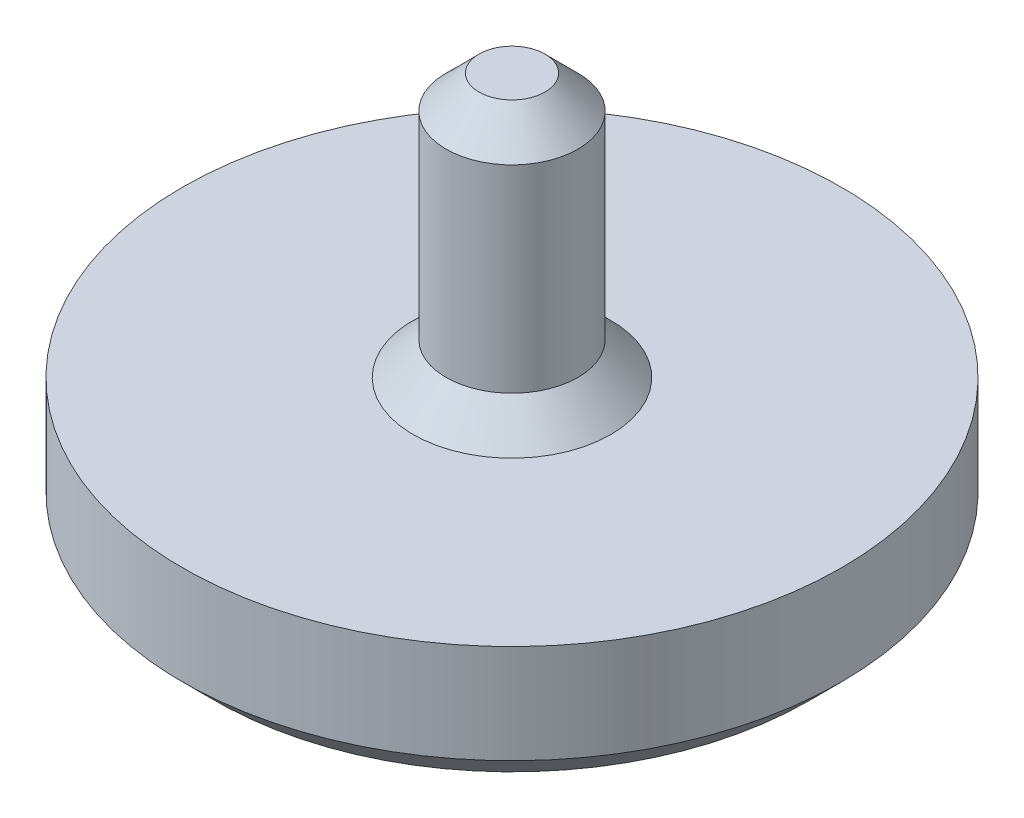
SolidWorks part; units mm, degrees
ref_plane "Front Plane" through (0, 0, 0) normal (0, 0, 1) x (1, 0, 0)
ref_plane "Top Plane" through (0, 0, 0) normal (0, 1, 0) x (1, 0, 0)
ref_plane "Right Plane" through (0, 0, 0) normal (1, 0, 0) x (0, 0, -1)
sketch "Sketch1" plane through (0, 0, 0) normal (0, 0, 1) x (1, 0, 0)
  line L0 (0, 0) -> (0, 4) construction
  line L1 (0, -55) -> (0, 55) construction
  line L2 (0, 4) -> (-1, 4)
  line L3 (-1, 4) -> (-1, 0)
  line L4 (55, 0) -> (-55, 0) construction
  line L5 (-1, 0) -> (-5, 0)
  line L6 (-5, 0) -> (-5, -2)
  line L7 (-5, -2) -> (0, -2)
  line L8 (0, -2) -> (0, 4)
  dimension "D1" = 1
  dimension "D2" = 4
  dimension "D3" = 2
  dimension "D4" = 5
revolve "Revolve1" add sketch "Sketch1" angle 360 about L0
chamfer "Chamfer1" distance 0.5 angle 45 3 edges at (5, -2, 0) (1, 0, 0) (1, 4, 0)
